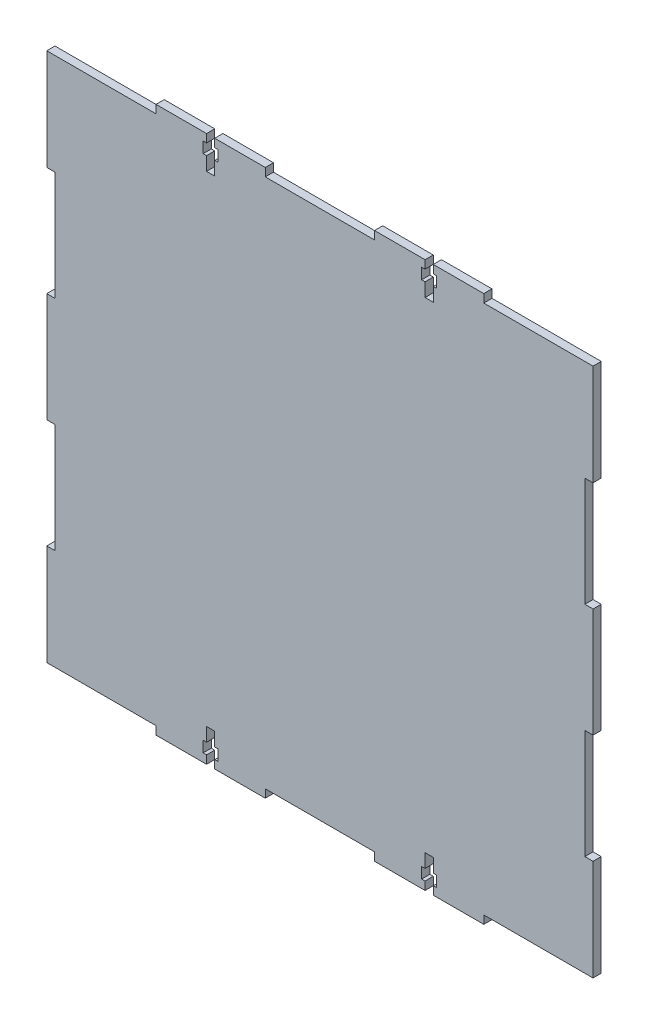
SolidWorks part; units mm, degrees
ref_plane "前视基准面" through (0, 0, 0) normal (0, 0, 1) x (1, 0, 0)
ref_plane "上视基准面" through (0, 0, 0) normal (0, 1, 0) x (1, 0, 0)
ref_plane "右视基准面" through (0, 0, 0) normal (1, 0, 0) x (0, 0, -1)
sketch "草图1" plane through (0, 0, 0) normal (0, 0, 1) x (1, 0, 0)
  line L0 (100, 0) -> (100, -200)
  line L1 (0, 0) -> (200, 0)
  line L2 (0, 0) -> (0, -200)
  line L3 (0, -200) -> (200, -200)
  line L4 (200, 0) -> (200, -200)
  line L5 (0, 0) -> (40, 0)
  line L6 (0, 0) -> (0, -3)
  line L7 (0, -3) -> (40, -3)
  line L8 (40, 0) -> (40, -3)
  line L9 (0, -100) -> (200, -100)
  line L10 (80, 0) -> (80, -3)
  line L11 (80, 0) -> (120, 0)
  line L12 (120, 0) -> (120, -3)
  line L13 (80, -3) -> (120, -3)
  line L14 (160, 0) -> (160, -3)
  line L15 (160, 0) -> (200, 0)
  line L16 (200, 0) -> (200, -3)
  line L17 (160, -3) -> (200, -3)
  line L18 (0, 0) -> (80, 0) construction
  line L31 (200, -200) -> (200, -197)
  line L32 (200, -200) -> (160, -200)
  line L33 (160, -200) -> (160, -197)
  line L34 (200, -197) -> (160, -197)
  line L35 (120, -200) -> (120, -197)
  line L36 (120, -197) -> (80, -197)
  line L37 (80, -200) -> (80, -197)
  line L38 (120, -200) -> (80, -200)
  line L39 (40, -200) -> (40, -197)
  line L40 (40, -197) -> (0, -197)
  line L41 (0, -200) -> (0, -197)
  line L42 (40, -200) -> (0, -200)
  line L55 (0, -40) -> (3, -40) [skipped]
  line L56 (3, -40) -> (3, 0) [skipped]
  line L57 (0, 0) -> (3, 0) [skipped]
  line L58 (0, -40) -> (0, 0) [skipped]
  line L59 (0, -120) -> (3, -120) [skipped]
  line L60 (3, -120) -> (3, -80) [skipped]
  line L61 (0, -80) -> (3, -80) [skipped]
  line L62 (0, -120) -> (0, -80) [skipped]
  line L63 (0, -200) -> (3, -200) [skipped]
  line L64 (3, -200) -> (3, -160) [skipped]
  line L65 (0, -160) -> (3, -160) [skipped]
  line L66 (0, -200) -> (0, -160) [skipped]
  line L67 (197, -80) -> (197, -120) [skipped]
  line L68 (200, -80) -> (197, -80) [skipped]
  line L69 (200, -120) -> (197, -120) [skipped]
  line L70 (200, -80) -> (200, -120) [skipped]
  line L71 (200, 0) -> (197, 0) [skipped]
  line L72 (197, 0) -> (197, -40) [skipped]
  line L73 (200, -40) -> (197, -40) [skipped]
  line L74 (200, 0) -> (200, -40) [skipped]
  line L75 (200, -160) -> (197, -160) [skipped]
  line L76 (197, -160) -> (197, -200) [skipped]
  line L77 (200, -200) -> (197, -200) [skipped]
  line L78 (200, -160) -> (200, -200) [skipped]
  line L79 (200, -40) -> (197, -40)
  line L80 (200, -120) -> (197, -120)
  line L81 (200, -120) -> (200, -160)
  line L82 (200, -160) -> (197, -160)
  line L83 (197, -120) -> (197, -160)
  line L84 (197, -80) -> (197, -40)
  line L85 (200, -80) -> (197, -80)
  line L86 (200, -80) -> (200, -40)
  line L87 (0, -160) -> (3, -160)
  line L88 (3, -120) -> (3, -160)
  line L89 (0, -120) -> (3, -120)
  line L90 (0, -120) -> (0, -160)
  line L91 (0, -80) -> (0, -40)
  line L92 (0, -80) -> (3, -80)
  line L93 (3, -80) -> (3, -40)
  line L94 (0, -40) -> (3, -40)
  line L95 (142.75, -197) -> (137.25, -197)
  line L96 (58.5, -200) -> (61.5, -200)
  line L97 (58.5, -200) -> (58.5, -188)
  line L98 (58.5, -188) -> (61.5, -188)
  line L99 (61.5, -200) -> (61.5, -188)
  line L100 (57.25, -193) -> (62.75, -193)
  line L101 (57.25, -193) -> (57.25, -197)
  line L102 (57.25, -197) -> (62.75, -197)
  line L103 (62.75, -193) -> (62.75, -197)
  line L104 (137.25, -193) -> (137.25, -197)
  line L105 (142.75, -193) -> (137.25, -193)
  line L106 (142.75, -193) -> (142.75, -197)
  line L107 (141.5, -188) -> (138.5, -188)
  line L108 (138.5, -200) -> (138.5, -188)
  line L109 (141.5, -200) -> (138.5, -200)
  line L110 (141.5, -200) -> (141.5, -188)
  line L111 (142.75, -7) -> (142.75, -3)
  line L112 (142.75, -7) -> (137.25, -7)
  line L113 (137.25, -7) -> (137.25, -3)
  line L114 (142.75, -3) -> (137.25, -3)
  line L115 (141.5, 0) -> (141.5, -12)
  line L116 (141.5, 0) -> (138.5, 0)
  line L117 (138.5, 0) -> (138.5, -12)
  line L118 (141.5, -12) -> (138.5, -12)
  line L119 (58.5, -12) -> (61.5, -12)
  line L120 (61.5, 0) -> (61.5, -12)
  line L121 (58.5, 0) -> (61.5, 0)
  line L122 (58.5, 0) -> (58.5, -12)
  line L123 (57.25, -3) -> (62.75, -3)
  line L124 (62.75, -7) -> (62.75, -3)
  line L125 (57.25, -7) -> (62.75, -7)
  line L126 (57.25, -7) -> (57.25, -3)
  circle A0 centre (100, -100) radius 17.7588
  circle A1 centre (100, -100) radius 17.7588
  circle A2 centre (100, -100) radius 17.7588
  circle A3 centre (100, -100) radius 17.7588
  dimension "D1" = 200
  dimension "D2" = 200
  dimension "D3" = 40
  dimension "D4" = 3
  dimension "D6" = 80
  dimension "D8" = 3
  dimension "D9" = 40
  dimension "D10" = 40
  dimension "D11" = 3
  dimension "D12" = 12
  dimension "D13" = 18.5
  dimension "D14" = 3
  dimension "D15" = 5.5
  dimension "D16" = 4
  dimension "D17" = 1.25
  dimension "D5" = 3
  dimension "D7" = 4
extrude "凸台-拉伸1" add sketch "草图1" along normal blind 3
